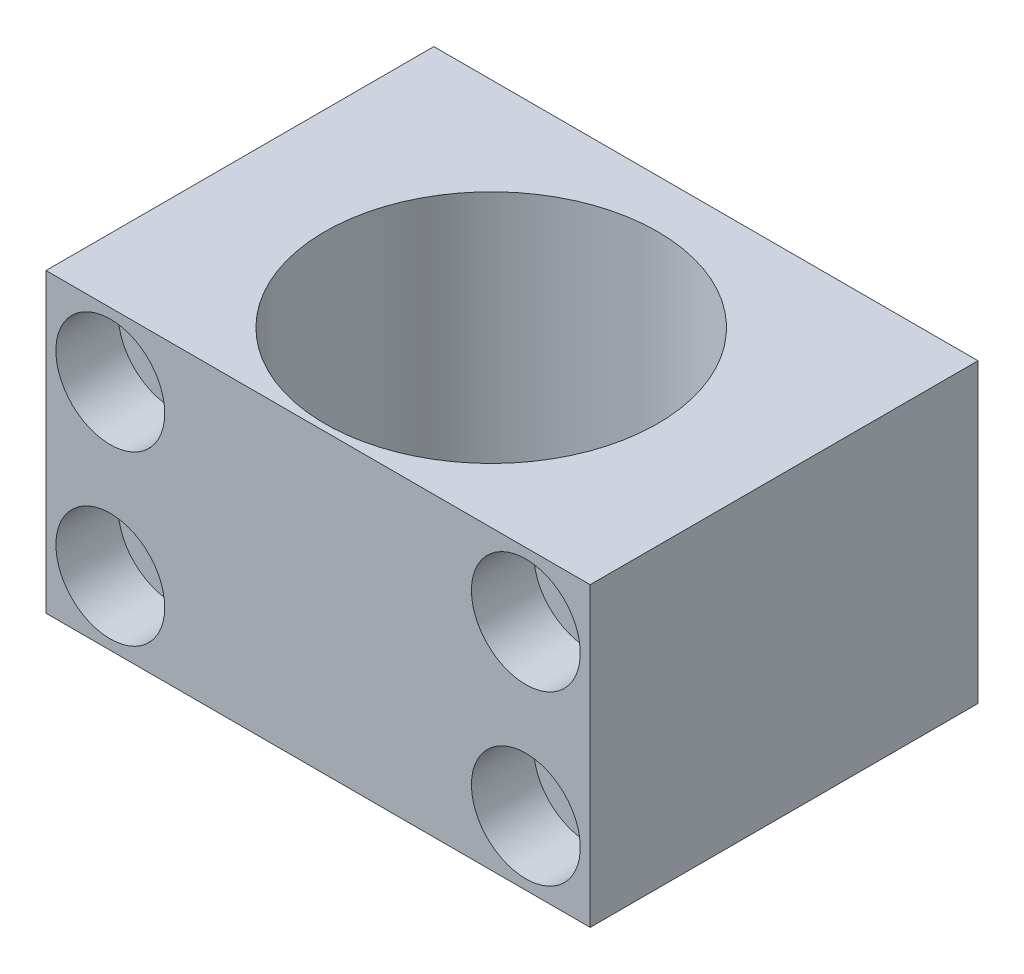
SolidWorks part; units mm, degrees
ref_plane "Front Plane" through (0, 0, 0) normal (0, 0, 1) x (1, 0, 0)
ref_plane "Top Plane" through (0, 0, 0) normal (0, 1, 0) x (1, 0, 0)
ref_plane "Right Plane" through (0, 0, 0) normal (1, 0, 0) x (0, 0, -1)
sketch "Sketch1" plane through (0, 0, 0) normal (0, 1, 0) x (1, 0, 0)
  line L1 (27.5, 19.6) -> (-27.5, 19.6)
  line L2 (27.5, 19.6) -> (27.5, -19.6)
  line L3 (27.5, -19.6) -> (-27.5, -19.6)
  line L4 (-27.5, 19.6) -> (-27.5, -19.6)
  line L5 (27.5, 19.6) -> (-27.5, -19.6) construction
  line L6 (27.5, -19.6) -> (-27.5, 19.6) construction
  point P0 (0, 0)
  dimension "D1" = 55
  dimension "D2" = 39.2
extrude "Boss-Extrude1" add sketch "Sketch1" along normal blind 30
sketch "Sketch2" plane through (0, 0, 0) normal (0, -1, 0) x (1, 0, 0)
  line L0 (-27.5, 19.6) -> (27.5, 19.6) construction
  circle A0 centre (0, 2.1) radius 16.8183
  point P5 (-59.7781, 8.6249)
  dimension "D1" = 17.5
extrude "Cut-Extrude1" cut sketch "Sketch2" against normal through all
sketch "Sketch3" plane through (0, 0, 19.6) normal (0, 0, 1) x (1, 0, 0)
  line L0 (-27.5, 30) -> (-27.5, 0) construction
  line L1 (-27.5, 30) -> (27.5, 30) construction
  line L2 (-27.5, 0) -> (27.5, 0) construction
  line L3 (0, -16.5) -> (0, 16.5) construction
  circle A0 centre (-21, 23.5) radius 5.5
  circle A1 centre (-21, 6.5) radius 5.5
  circle A2 centre (21, 6.5) radius 5.5
  circle A3 centre (21, 23.5) radius 5.5
  dimension "D1" = 6.5
  dimension "D3" = 6.5
  dimension "D2" = 6.5
  dimension "D4" = 6.5
extrude "Cut-Extrude2" cut sketch "Sketch3" against normal blind 6.3
sketch "Sketch5" plane through (0, 0, 19.6) normal (0, 0, 1) x (1, 0, 0)
  line L0 (0, -16.5) -> (0, 16.5) construction
  circle A0 centre (-21, 6.5) radius 3.25
  circle A1 centre (-21, 23.5) radius 3.25
  circle A2 centre (21, 23.5) radius 3.25
  circle A3 centre (21, 6.5) radius 3.25
extrude "Cut-Extrude3" cut sketch "Sketch5" against normal through all
